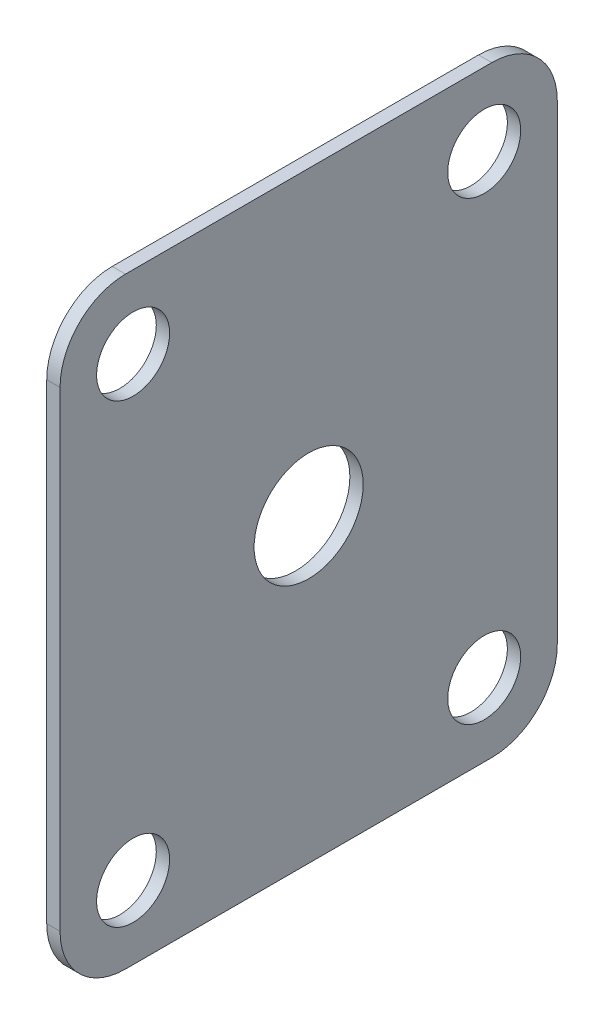
SolidWorks part; units mm, degrees
material "6061-T6 (SS)"
ref_plane "Front Plane" through (0, 0, 0) normal (0, 0, 1) x (1, 0, 0)
ref_plane "Top Plane" through (0, 0, 0) normal (0, 1, 0) x (1, 0, 0)
ref_plane "Right Plane" through (0, 0, 0) normal (1, 0, 0) x (0, 0, -1)
sketch "Sketch1" plane through (0, 0, 0) normal (1, 0, 0) x (0, 0, -1)
  line L1 (-28.956, -35.052) -> (28.956, -35.052)
  line L2 (-28.956, -35.052) -> (-28.956, 35.052)
  line L3 (-28.956, 35.052) -> (28.956, 35.052)
  line L4 (28.956, -35.052) -> (28.956, 35.052)
  line L5 (-28.956, -35.052) -> (28.956, 35.052) construction
  line L6 (-28.956, 35.052) -> (28.956, -35.052) construction
  line L7 (-20.447, -26.543) -> (20.447, -26.543) construction
  line L8 (-20.447, -26.543) -> (-20.447, 26.543) construction
  line L9 (-20.447, 26.543) -> (20.447, 26.543) construction
  line L10 (20.447, -26.543) -> (20.447, 26.543) construction
  line L11 (-20.447, -26.543) -> (20.447, 26.543) construction
  line L12 (-20.447, 26.543) -> (20.447, -26.543) construction
  circle A0 centre (-20.447, 26.543) radius 4.25
  circle A1 centre (20.447, 26.543) radius 4.25
  circle A2 centre (20.447, -26.543) radius 4.25
  circle A3 centre (-20.447, -26.543) radius 4.25
  circle A4 centre (0, 0) radius 6.35
  point P0 (0, 0)
  point P6 (0, 0)
  dimension "D5" = 8.5
  dimension "D6" = 12.7
  dimension "D1" = 57.912
  dimension "D2" = 40.894
  dimension "D3" = 70.104
  dimension "D4" = 53.086
extrude "Boss-Extrude1" add sketch "Sketch1" along normal blind 1.5494
fillet "Fillet1" radius 7.62 4 edges at (0.7747, -35.052, -28.956) (0.7747, -35.052, 28.956) (0.7747, 35.052, -28.956) (0.7747, 35.052, 28.956)
